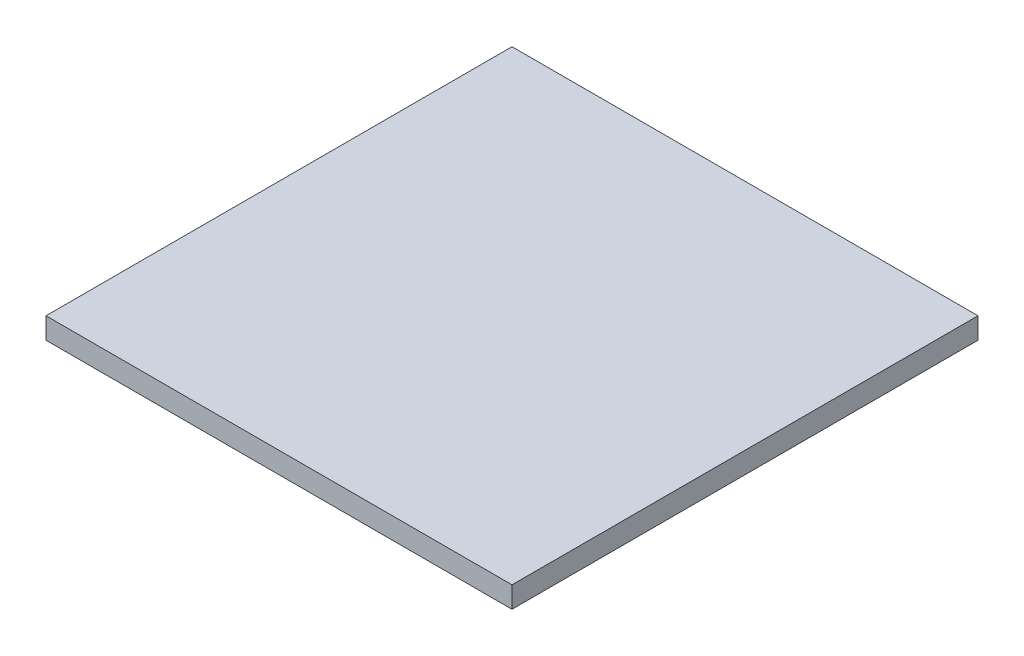
SolidWorks part; units mm, degrees
material "Silicon"
ref_plane "Front Plane" through (0, 0, 0) normal (0, 0, 1) x (1, 0, 0)
ref_plane "Top Plane" through (0, 0, 0) normal (0, 1, 0) x (1, 0, 0)
ref_plane "Right Plane" through (0, 0, 0) normal (1, 0, 0) x (0, 0, -1)
sketch "Sketch1" plane through (0, 0, 0) normal (0, 1, 0) x (1, 0, 0)
  line L1 (0, 0) -> (10, 0)
  line L2 (0, 0) -> (0, 10)
  line L3 (0, 10) -> (10, 10)
  line L4 (10, 0) -> (10, 10)
  dimension "D1" = 10
  dimension "D2" = 10
extrude "Boss-Extrude1" add sketch "Sketch1" along normal blind 0.455
